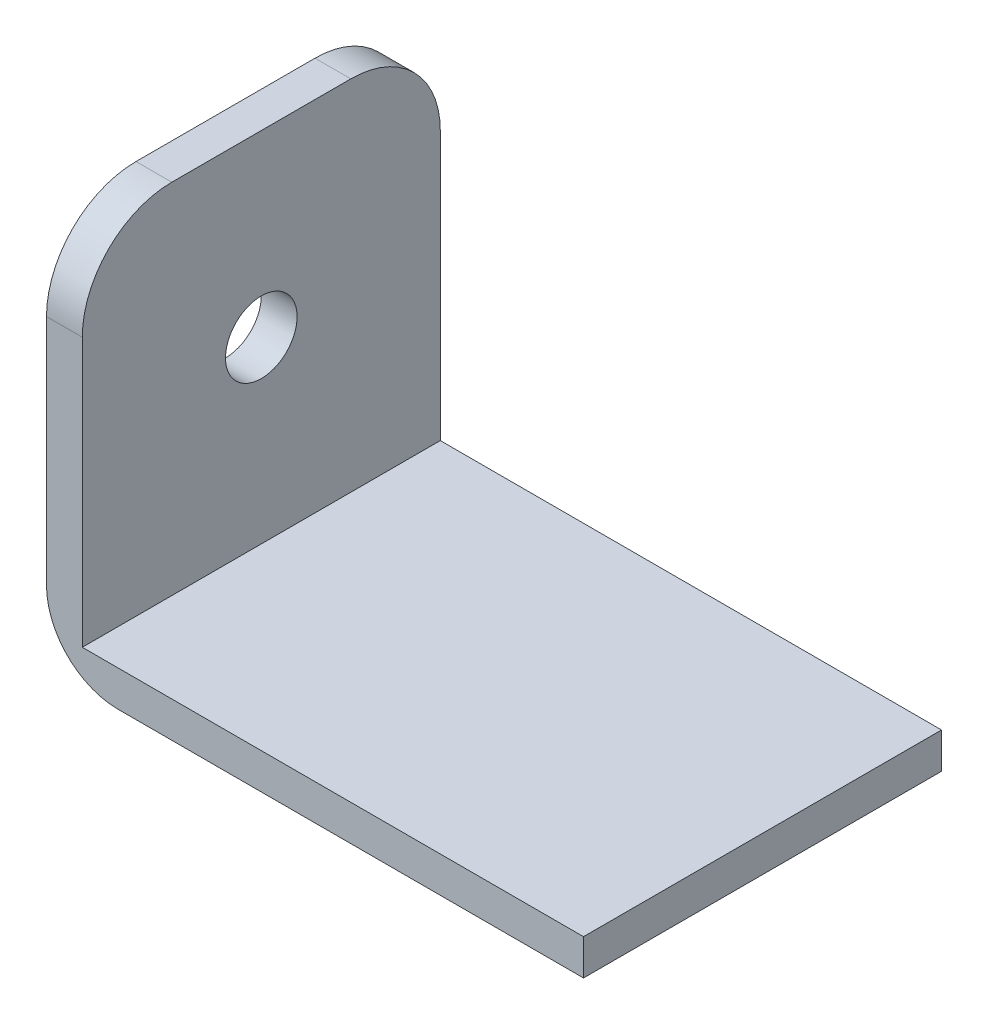
SolidWorks part; units mm, degrees
ref_plane "Front Plane" through (0, 0, 0) normal (0, 0, 1) x (1, 0, 0)
ref_plane "Top Plane" through (0, 0, 0) normal (0, 1, 0) x (1, 0, 0)
ref_plane "Right Plane" through (0, 0, 0) normal (1, 0, 0) x (0, 0, -1)
sketch "Sketch1" plane through (0, 0, 0) normal (0, 0, 1) x (1, 0, 0)
  line L1 (0, 0) -> (5, 0)
  line L2 (0, 0) -> (0, -55)
  line L3 (0, -55) -> (5, -55)
  line L4 (5, 0) -> (5, -55)
  line L5 (0, -55) -> (75, -55)
  line L6 (0, -55) -> (0, -50)
  line L7 (0, -50) -> (75, -50)
  line L8 (75, -55) -> (75, -50)
  dimension "D1" = 5
  dimension "D2" = 55
  dimension "D3" = 5
  dimension "D4" = 75
extrude "Boss-Extrude1" add sketch "Sketch1" along normal blind 50 contours L2 L7 L4 L1 | L5 L8 L7 L4 | L7 L2 L3 L4
sketch "Sketch2" plane through (0, 0, 0) normal (-1, 0, 0) x (0, 0, 1)
  line L0 (50, 0) -> (50, -55) construction
  line L1 (0, 0) -> (50, 0)
  line L2 (0, 0) -> (0, -50)
  line L3 (0, -50) -> (50, -50)
  line L4 (50, 0) -> (50, -50)
  circle A0 centre (25, -25) radius 5
  dimension "D1" = 50
extrude "Cut-Extrude1" cut sketch "Sketch2" against normal blind 5 contours A0
fillet "Fillet1" radius 10 1 edges at (0, -55, 25)
fillet "Fillet2" radius 12.5 2 edges at (2.5, 0, 0) (2.5, 0, 50)
